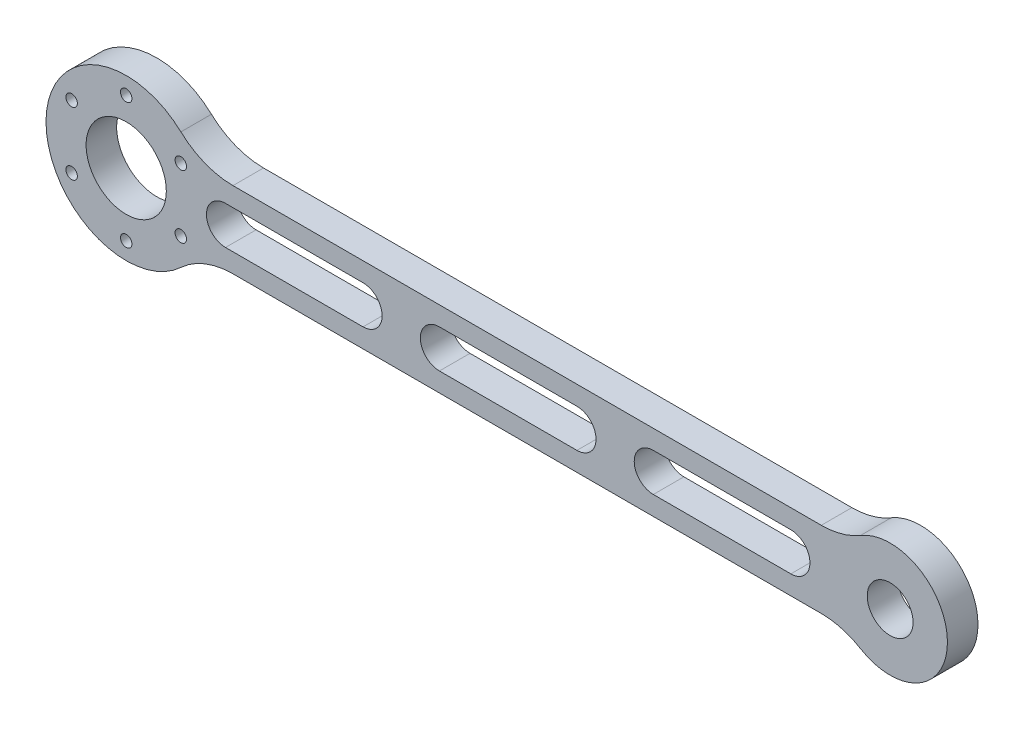
SolidWorks part; units mm, degrees
material "7075-T6，板材(SS)"
ref_plane "前视基准面" through (0, 0, 0) normal (0, 0, 1) x (1, 0, 0)
ref_plane "上视基准面" through (0, 0, 0) normal (0, 1, 0) x (1, 0, 0)
ref_plane "右视基准面" through (0, 0, 0) normal (1, 0, 0) x (0, 0, -1)
sketch "草图1" plane through (0, 0, 0) normal (0, 0, 1) x (1, 0, 0)
  line L0 (0, 0) -> (200, 0) construction
  line L1 (0, 0) -> (0, 10) construction
  line L6 (0, 10) -> (200, 10)
  line L7 (0, 10) -> (0, -10)
  line L8 (0, -10) -> (200, -10)
  line L9 (200, 10) -> (200, -10)
  circle A1 centre (200, 0) radius 15
  circle A2 centre (0, 0) radius 15
  dimension "D1" = 30
  dimension "D3" = 30
  dimension "D2" = 200
  dimension "D4" = 10
  dimension "D5" = 20
  dimension "D6" = 200
extrude "凸台-拉伸1" add sketch "草图1" along normal blind 8 contours L6 A2 L8 L7 | L8 A2 L6 L7 | A2 L8 A1 L6 | L8 A1 L6 L9 | L6 A1 L8 L9
fillet "圆角1" radius 20 4 edges at (188.8197, 10, 4) (188.8197, -10, 4) (11.1803, -10, 4) (11.1803, 10, 4)
sketch "草图5" plane through (0, 0, 8) normal (0, 0, 1) x (1, 0, 0)
  circle A0 centre (0, 0) radius 10.5
  circle A1 centre (200, 0) radius 6
  dimension "D1" = 21
  dimension "D2" = 12
extrude "切除-拉伸4" cut sketch "草图5" against normal blind 10
sketch "草图6" plane through (0, 0, 8) normal (0, 0, 1) x (1, 0, 0)
  line L0 (100, 10) -> (100, -10) construction
  line L1 (18.0278, 10) -> (181.9722, 10) construction
  line L2 (18.0278, -10) -> (181.9722, -10) construction
  line L3 (174, -5) -> (138, -5)
  line L4 (118, -5) -> (82, -5)
  line L5 (118, -5) -> (118, 5)
  line L6 (118, 5) -> (82, 5)
  line L7 (82, -5) -> (82, 5)
  line L8 (118, -5) -> (82, 5) construction
  line L9 (118, 5) -> (82, -5) construction
  line L10 (174, -5) -> (174, 5)
  line L11 (174, 5) -> (138, 5)
  line L12 (138, -5) -> (138, 5)
  line L13 (156, 10) -> (156, -10) construction
  line L14 (174, -5) -> (138, 5) construction
  line L15 (174, 5) -> (138, -5) construction
  line L16 (62, -5) -> (26, -5)
  line L17 (62, -5) -> (62, 5)
  line L18 (62, 5) -> (26, 5)
  line L19 (26, -5) -> (26, 5)
  line L20 (44, 10) -> (44, -10) construction
  line L21 (62, -5) -> (26, 5) construction
  line L22 (62, 5) -> (26, -5) construction
  circle A0 centre (118, 0) radius 5
  circle A1 centre (82, 0) radius 5
  circle A2 centre (174, 0) radius 5
  circle A3 centre (138, 0) radius 5
  circle A4 centre (62, 0) radius 5
  circle A5 centre (26, 0) radius 5
  point P6 (100, 2.5)
  point P7 (100, 0)
  point P19 (156, 2.5)
  point P20 (156, 0)
  point P32 (44, 2.5)
  point P33 (44, 0)
  dimension "D3" = 2
  dimension "D4" = 2
  dimension "D1" = 10
  dimension "D2" = 36
extrude "切除-拉伸5" cut sketch "草图6" against normal blind 10 contours L12 A3 | L12 A3 | A3 L3 A2 L11 | L10 A2 | L10 A2 | L5 A0 | L5 A0 | A1 L4 A0 L6 | L7 A1 | L7 A1 | L17 A4 | L17 A4 | A5 L16 A4 L18 | L19 A5 | L19 A5
sketch "草图9" plane through (0, 0, 0) normal (0, 0, -1) x (-1, 0, 0)
  line L1 (-18.4662, 10) -> (-18.4662, -10)
  arc A0 (-18.4662, -10) -> (-18.4662, 10) centre (0, 0) ccw
  circle A2 centre (0, 0) radius 10.5 construction
  circle A7 centre (0, 0) radius 10.5
  dimension "D1" = 42
extrude "凸台-拉伸3" add sketch "草图9" against normal blind 8
fillet "圆角2" radius 20 2 edges at (18.4662, -10, 4) (18.4662, 10, 4)
sketch "草图10" plane through (0, 0, 0) normal (0, 0, -1) x (-1, 0, 0)
  line L0 (0, 0) -> (11.6673, -11.6673) construction
  line L1 (0, 0) -> (11.6673, 11.6673) construction
  circle A0 centre (0, 0) radius 16.5 construction
  circle A1 centre (0, 16.5) radius 1.5
  circle A5 centre (14.2894, 8.25) radius 1.5
  circle A8 centre (14.2894, -8.25) radius 1.5
  circle A9 centre (0, -16.5) radius 1.5
  circle A10 centre (-14.2894, -8.25) radius 1.5
  circle A11 centre (-14.2894, 8.25) radius 1.5
  point P14 (0, 0)
  point P21 (0, 0)
  dimension "D1" = 33
  dimension "D2" = 3
  dimension "D3" = 6
extrude "切除-拉伸7" cut sketch "草图10" against normal blind 8
